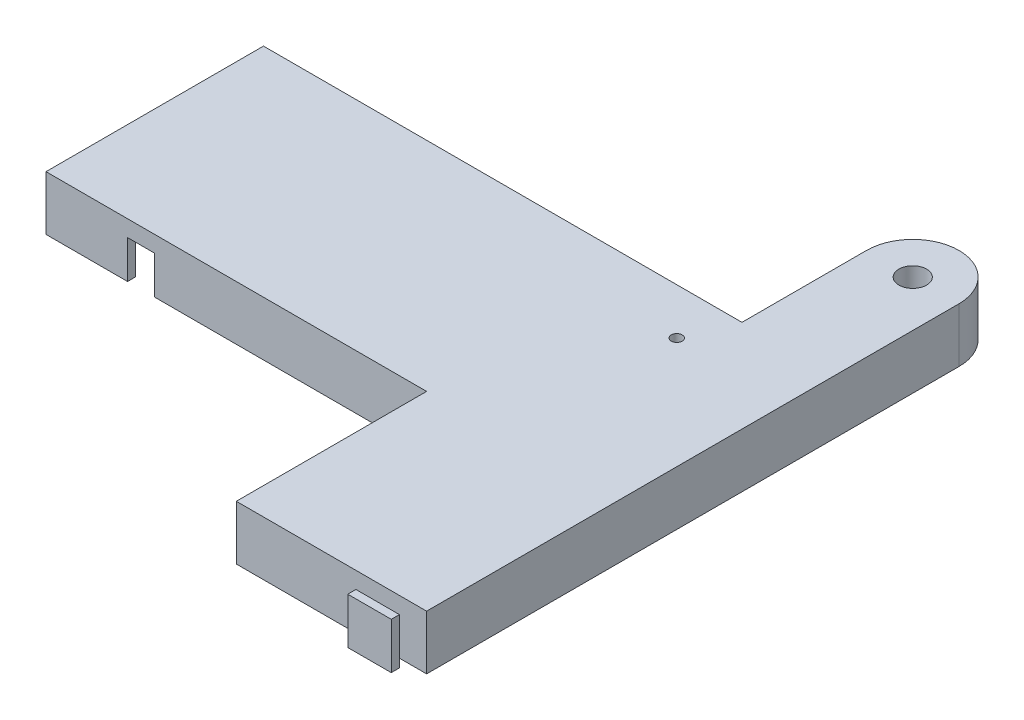
SolidWorks part; units mm, degrees
ref_plane "Front Plane" through (0, 0, 0) normal (0, 0, 1) x (1, 0, 0)
ref_plane "Top Plane" through (0, 0, 0) normal (0, 1, 0) x (1, 0, 0)
ref_plane "Right Plane" through (0, 0, 0) normal (1, 0, 0) x (0, 0, -1)
sketch "CornerSketch1" plane through (0, 0, 0) normal (0, 1, 0) x (1, 0, 0)
  line L0 (210, -70) -> (140, -70)
  line L2 (0, 80) -> (176, 80)
  line L5 (140, -70) -> (140, 0)
  line L6 (140, 0) -> (0, 0)
  line L7 (0, 80) -> (0, 0)
  line L8 (176, 125.825) -> (176, 80)
  line L10 (210, 125.825) -> (210, -70)
  arc A0 (210, 125.825) -> (176, 125.825) centre (193, 125.825) ccw
  dimension "D3" = 34
  dimension "D4" = 70
  dimension "D6" = 45.825
  dimension "D2" = 210
  dimension "D5" = 150
  dimension "D7" = 80
extrude "CornerBoss-Extrude1" add sketch "CornerSketch1" along normal blind 20
shell "Shell1" thickness 3
sketch "PadSketch2" plane through (0, 17, 0) normal (0, -1, 0) x (1, 0, 0)
  line L0 (210, 70) -> (210, -125.825) construction
  line L1 (176, -80) -> (0, -80) construction
  circle A0 centre (193, -125.825) radius 12
  circle A1 centre (169, -63) radius 5
  dimension "D2" = 10
  dimension "D1" = 24
  dimension "D3" = 41
  dimension "D4" = 17
extrude "PadBoss-Extrude2" add sketch "PadSketch2" along normal blind 10
sketch "StepperRodHoleSketch3" plane through (0, 7, 0) normal (0, -1, 0) x (1, 0, 0)
  circle A0 centre (193, -125.825) radius 5.1
  circle A1 centre (169, -63) radius 2
  dimension "D1" = 10.2
  dimension "D2" = 4
extrude "StepperRodHoleCut-Extrude1" cut sketch "StepperRodHoleSketch3" against normal through all
sketch "ThreadedNutMountHolesSketch4" plane through (0, 7, 0) normal (0, -1, 0) x (-1, 0, 0)
  circle A8 centre (-193, 133.825) radius 2
  circle A9 centre (-185, 125.825) radius 2
  circle A10 centre (-201, 125.825) radius 2
  circle A11 centre (-193, 117.825) radius 2
  dimension "D1" = 4
  dimension "D3" = 16
  dimension "D4" = 8
  dimension "D5" = 16
  dimension "D2" = 8
extrude "ThreadedNutMountHolesCut-Extrude2" cut sketch "ThreadedNutMountHolesSketch4" against normal blind 10
sketch "TLPegHoleSketch1" plane through (0, 0, 0) normal (-1, 0, 0) x (0, 0, 1)
  line L1 (-70, 14) -> (-60, 14)
  line L2 (-70, 14) -> (-70, 0)
  line L3 (-70, 0) -> (-60, 0)
  line L4 (-60, 14) -> (-60, 0)
  line L7 (-80, 0) -> (0, 0) construction
  line L8 (-80, 20) -> (-80, 0) construction
  dimension "D2" = 10
  dimension "D1" = 10
  dimension "D3" = 14
extrude "TLPegHoleCut-Extrude1" cut sketch "TLPegHoleSketch1" against normal blind 3
sketch "BottomPegSketch2" plane through (0, 0, 70) normal (0, 0, 1) x (1, 0, 0)
  line L1 (190.1, 13.9) -> (199.9, 13.9)
  line L2 (190.1, 13.9) -> (190.1, 0)
  line L3 (190.1, 0) -> (199.9, 0)
  line L4 (199.9, 13.9) -> (199.9, 0)
  line L6 (210, 20) -> (210, 0) construction
  line L7 (140, 0) -> (210, 0) construction
  dimension "D2" = 13.9
  dimension "D3" = 9.8
  dimension "D1" = 10.1
extrude "BottomPegBoss-Extrude1" add sketch "BottomPegSketch2" along normal blind 3.1
sketch "BottomPegCapSketch3" plane through (0, 0, 73.1) normal (0, 0, 1) x (1, 0, 0)
  line L1 (187.1, 17) -> (203.1, 17)
  line L2 (187.1, 17) -> (187.1, 0)
  line L3 (187.1, 0) -> (203.1, 0)
  line L4 (203.1, 17) -> (203.1, 0)
  line L6 (140, 0) -> (190.1, 0) construction
  line L7 (190.1, 13.9) -> (190.1, 0) construction
  dimension "D1" = 16
  dimension "D3" = 17
  dimension "D2" = 3
extrude "BottomPegCapBoss-Extrude2" add sketch "BottomPegCapSketch3" along normal blind 3
sketch "BedCenterHoleCutSketch1" plane through (0, 0, 0) normal (0, 0, 1) x (1, 0, 0)
  line L0 (0, 0) -> (140, 0) construction
  line L1 (30, 14) -> (40, 14)
  line L2 (30, 14) -> (30, 0)
  line L3 (30, 0) -> (40, 0)
  line L4 (40, 14) -> (40, 0)
  line L5 (140, 20) -> (140, 0) construction
  dimension "D2" = 10
  dimension "D1" = 14
  dimension "D3" = 100
extrude "BedCenterHoleCut-Extrude1" cut sketch "BedCenterHoleCutSketch1" against normal blind 3
equation "\"BedThickness\"= 20mm"
equation "\"BedToBuildPlateStandoffHolesDistanceFromLeftOrRight\"= \"BuildPlateStandoffHolesDistanceFromLeftOrRight\" + \"BedIncreasedByWidth\" / 2'Equals 17"
equation "\"BedToBuildPlateStandoffHolesDistanceFromBack\"= \"BuildPlateStandoffHolesDistanceFromBack\" + \"BedIncreasedByLength\" / 2'Equals 41"
equation "\"BedLLongSide\"= \"BedThirdSize\" * 3'Equals 210"
equation "\"BedLShortSide\"= \"BedThirdSize\" * 2'Equals 140"
equation "\"BedIncreasedByWidth\"= 20mm"
equation "\"BedIncreasedByLength\"= 0mm"
equation "\"BedThirdSize\"= 70mm"
equation "\"BedOverlap\"= 20mm"
equation "\"D3@TLPegHoleSketch1\"=\"BedPegHoleHeight\""
equation "\"StandardWallThickness\"= 3mm"
equation "\"D1@CornerBoss-Extrude1\"=\"BedThickness\""
equation "\"D1@TLPegHoleCut-Extrude1\" = \"StandardWallThickness\""
equation "\"D1@BottomPegBoss-Extrude1\"=\"BedPegBoss\""
equation "\"D2@BottomPegCapSketch3\"=\"StandardWallThickness\""
equation "\"D1@BottomPegCapBoss-Extrude2\" = \"StandardWallThickness\""
equation "\"LeadScrewNutPadSize\"= \"LeadScrewNutMountingHoleFlangeDiameter\" + 2mm'Equals 24"
equation "\"BedToBuildPlateStandoffPadSize\"= 10mm"
equation "\"D1@PadSketch2\" = \"LeadScrewNutPadSize\""
equation "\"D2@PadSketch2\" = \"BedToBuildPlateStandoffPadSize\""
equation "\"D3@PadSketch2\"=\"BedToBuildPlateStandoffHolesDistanceFromBack\""
equation "\"D4@PadSketch2\"=\"BedToBuildPlateStandoffHolesDistanceFromLeftOrRight\""
equation "\"D2@StepperRodHoleSketch3\"=\"M3HeatInsertHoleDiameter\""
equation "\"BuildPlateStandoffHolesDistanceFromLeftOrRight\"= 7mm"
equation "\"BuildPlateStandoffHolesDistanceFromBack\"= 41mm"
equation "\"D1@StepperRodHoleSketch3\"=\"LeadScrewNutInnerShaftFlangeDiameter\""
equation "\"BedLWidth\"= \"BedThirdSize\"'Equals 70"
equation "\"D4@CornerSketch1\"=\"BedLWidth\" + \"BedIncreasedByLength\"/2"
equation "\"D2@CornerSketch1\"=\"BedLLongSide\""
equation "\"D7@CornerSketch1\"=\"BedLWidth\" +\"BedOverlap\"/2"
equation "\"DistanceFromBedSideToStepperHole\"= ( \"DistanceBetweenLeftToRightStepperHoles\" - \"BedWidth\" ) / 2'Equals 45.825"
equation "\"RailThickness\"= .125in'Spec"
equation "\"DistanceBetweenLeftToRightStepperHoles\"= \"FrontBackRailLength\" - \"StepperMountingHoleOffsetFromLeftOrRightSide\" * 2 - \"StepperMountingHoleDistance\"'Equals 461.65"
equation "\"BedInnerSquareWidth\"= \"BedThirdSize\" * 3'Equals 210"
equation "\"FrontBackRailLength\"= 510mm"
equation "\"StepperMountingHoleOffsetFromItsSide\"= 5.5mm'Spec"
equation "\"StepperMountingHoleOffsetFromLeftOrRightSide\"= \"StepperMountingHoleOffsetFromItsSide\" + \"RailThickness\""
equation "\"StepperMountingHoleDistance\"= 31mm'Spec"
equation "\"BedWidth\"= \"BedInnerSquareWidth\" + \"BedLWidth\" * 2 + \"BedIncreasedByWidth\"'Equals 370"
equation "\"D6@CornerSketch1\"=\"DistanceFromBedSideToStepperHole\""
equation "\"DistanceFromBedFrontToStepperHole\"= \"LeadScrewNutPadSize\" + 10mm"
equation "\"D3@CornerSketch1\"=\"DistanceFromBedFrontToStepperHole\""
equation "\"D5@CornerSketch1\"=\"BedLShortSide\" +\"BedIncreasedByWidth\"/2"
equation "\"LeadScrewNutInnerShaftFlangeDiameter\"= 10.2mm'Spec"
equation "\"LeadScrewNutMountHoleDiameter\"= \"M3HeatInsertHoleDiameter\""
equation "\"LeadScrewNutMountingHoleFlangeDiameter\"= 22mm'Spec"
equation "\"LeadScrewNutMountingHoleDistance\"= 16mm'Spec"
equation "\"D3@ThreadedNutMountHolesSketch4\"=\"LeadScrewNutMountingHoleDistance\""
equation "\"D4@ThreadedNutMountHolesSketch4\"=\"LeadScrewNutMountingHoleDistance\"/2"
equation "\"D5@ThreadedNutMountHolesSketch4\"=\"LeadScrewNutMountingHoleDistance\""
equation "\"D2@ThreadedNutMountHolesSketch4\"=\"LeadScrewNutMountingHoleDistance\"/2"
equation "\"D1@ThreadedNutMountHolesSketch4\"=\"LeadScrewNutMountHoleDiameter\""
equation "\"LeadScrewNutPadDepth\"= \"BedThickness\" / 2'Equals 10"
equation "\"D1@ThreadedNutMountHolesCut-Extrude2\"=\"LeadScrewNutPadDepth\""
equation "\"D1@PadBoss-Extrude2\"= \"LeadScrewNutPadDepth\""
equation "\"BedPegHoleWidth\"= 10mm"
equation "\"BedPegHoleHeight\"= \"BedThickness\" - \"StandardWallThickness\" * 2'Equals 14"
equation "\"BedPegWidth\"= \"BedPegHoleWidth\" - .1mm * 2'For easier assembly"
equation "\"BedPegHeight\"= \"BedPegHoleHeight\" - .1mm'For easier assembly"
equation "\"BedTopPegOffsetFromSide\"= 10mm"
equation "\"BedPegBoss\"= \"StandardWallThickness\" + .1mm'For easier assembly"
equation "\"BedPegCapHeight\"= \"BedThickness\" - \"StandardWallThickness\"'Equals 17"
equation "\"BedPegCapWidth\"= \"BedThickness\" / 2 + \"StandardWallThickness\" * 2'Equals 16"
equation "\"D1@TLPegHoleSketch1\"=\"BedTopPegOffsetFromSide\""
equation "\"D2@TLPegHoleSketch1\"=\"BedPegHoleWidth\""
equation "\"D3@BottomPegSketch2\"=\"BedPegWidth\""
equation "\"D2@BottomPegSketch2\"=\"BedPegHeight\""
equation "\"D1@BottomPegCapSketch3\"=\"BedPegCapWidth\""
equation "\"D3@BottomPegCapSketch3\"=\"BedPegCapHeight\""
equation "\"D1@BedCenterHoleCutSketch1\" = \"BedPegHoleHeight\""
equation "\"D2@BedCenterHoleCutSketch1\" = \"BedPegHoleWidth\""
equation "\"D3@BedCenterHoleCutSketch1\" = \"BedInnerSquareWidth\" / 2 - \"BedPegHoleWidth\" / 2"
equation "\"D1@BedCenterHoleCut-Extrude1\"=\"StandardWallThickness\""
equation "\"M3HeatInsertHoleDiameter\"= 4mm'Spec"
